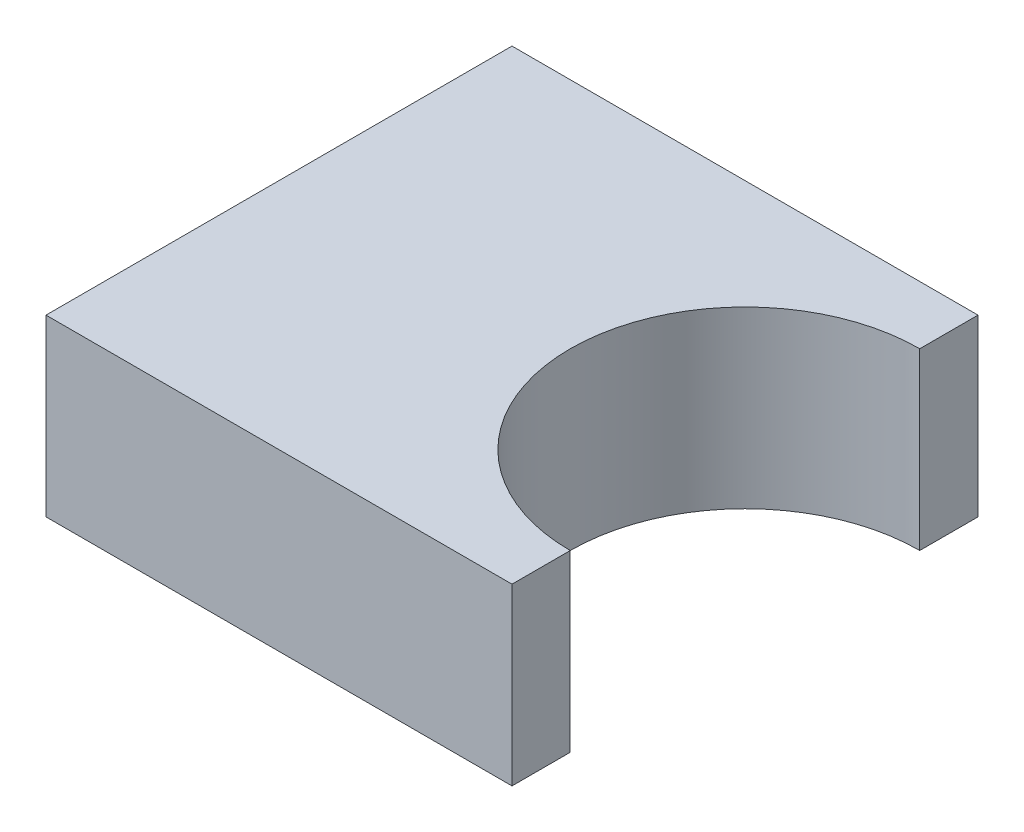
SolidWorks part; units mm, degrees
ref_plane "Front Plane" through (0, 0, 0) normal (0, 0, 1) x (1, 0, 0)
ref_plane "Top Plane" through (0, 0, 0) normal (0, 1, 0) x (1, 0, 0)
ref_plane "Right Plane" through (0, 0, 0) normal (1, 0, 0) x (0, 0, -1)
sketch "Sketch1" plane through (0, 0, 0) normal (0, 0, 1) x (1, 0, 0)
  line L1 (0, 0) -> (800, 0)
  line L2 (0, 0) -> (0, 300)
  line L3 (0, 300) -> (800, 300)
  line L4 (800, 0) -> (800, 300)
  dimension "D1" = 800
  dimension "D2" = 300
extrude "Boss-Extrude1" add sketch "Sketch1" along normal blind 800
sketch "Sketch2" plane through (0, 300, 0) normal (0, 1, 0) x (1, 0, 0)
  line L0 (800, -800) -> (800, 0) construction
  circle A0 centre (800, -400) radius 300
  dimension "D1" = 600
extrude "Cut-Extrude1" cut sketch "Sketch2" against normal blind 500
